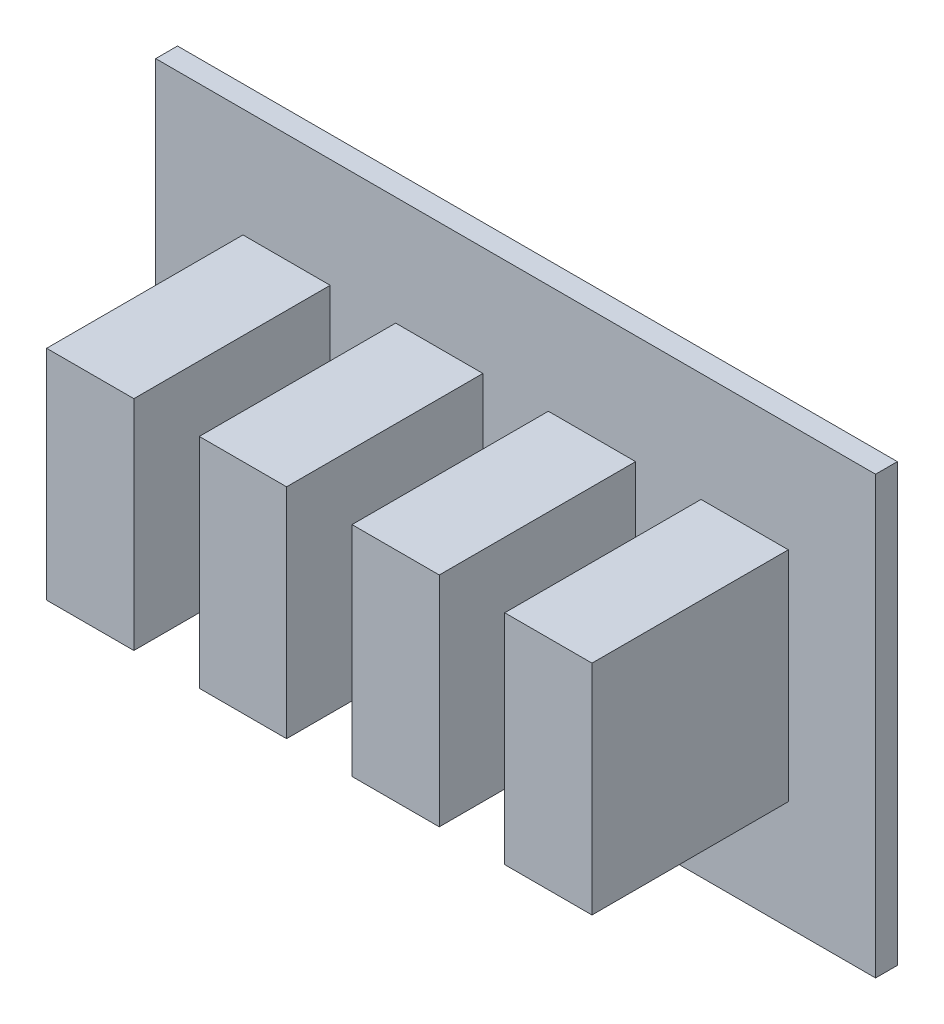
SolidWorks part; units mm, degrees
ref_plane "Plan de face" through (0, 0, 0) normal (0, 0, 1) x (1, 0, 0)
ref_plane "Plan de dessus" through (0, 0, 0) normal (0, 1, 0) x (1, 0, 0)
ref_plane "Plan de droite" through (0, 0, 0) normal (1, 0, 0) x (0, 0, -1)
sketch "Esquisse2" plane through (0, 0, 0) normal (0, 0, 1) x (1, 0, 0)
  line L1 (0, 0) -> (3.3, 0)
  line L2 (0, 0) -> (0, 2)
  line L3 (0, 2) -> (3.3, 2)
  line L4 (3.3, 0) -> (3.3, 2)
  dimension "D1" = 3.3
  dimension "D2" = 2
extrude "Boss.-Extru.1" add sketch "Esquisse2" along normal blind 0.1
sketch "Esquisse3" plane through (0, 0, 0.1) normal (0, 0, 1) x (1, 0, 0)
  line L1 (0.4, 1.5) -> (0.8, 1.5)
  line L2 (0.4, 1.5) -> (0.4, 0.5)
  line L3 (0.4, 0.5) -> (0.8, 0.5)
  line L4 (0.8, 1.5) -> (0.8, 0.5)
  line L5 (3.3, 2) -> (0, 2) construction
  line L6 (1.1, 1.5) -> (1.1, 0.5)
  line L7 (1.1, 1.5) -> (1.5, 1.5)
  line L8 (1.5, 1.5) -> (1.5, 0.5)
  line L9 (1.1, 0.5) -> (1.5, 0.5)
  line L10 (1.8, 1.5) -> (1.8, 0.5)
  line L11 (1.8, 1.5) -> (2.2, 1.5)
  line L12 (2.2, 1.5) -> (2.2, 0.5)
  line L13 (1.8, 0.5) -> (2.2, 0.5)
  line L14 (2.5, 1.5) -> (2.5, 0.5)
  line L15 (2.5, 1.5) -> (2.9, 1.5)
  line L16 (2.9, 1.5) -> (2.9, 0.5)
  line L17 (2.5, 0.5) -> (2.9, 0.5)
  line L18 (0.4, 1.5) -> (1.1, 1.5) construction
  line L19 (0.4, 0.5) -> (0, 0.5) construction
  line L20 (0, 2) -> (0, 0) construction
  line L21 (2.9, 0.5) -> (3.3, 0.5) construction
  line L22 (3.3, 0) -> (3.3, 2) construction
  dimension "D1" = 0.4
  dimension "D2" = 1
  dimension "D4" = 0.5
  dimension "D6" = 0.7
  dimension "D5" = 4
extrude "Boss.-Extru.2" add sketch "Esquisse3" along normal blind 0.9
